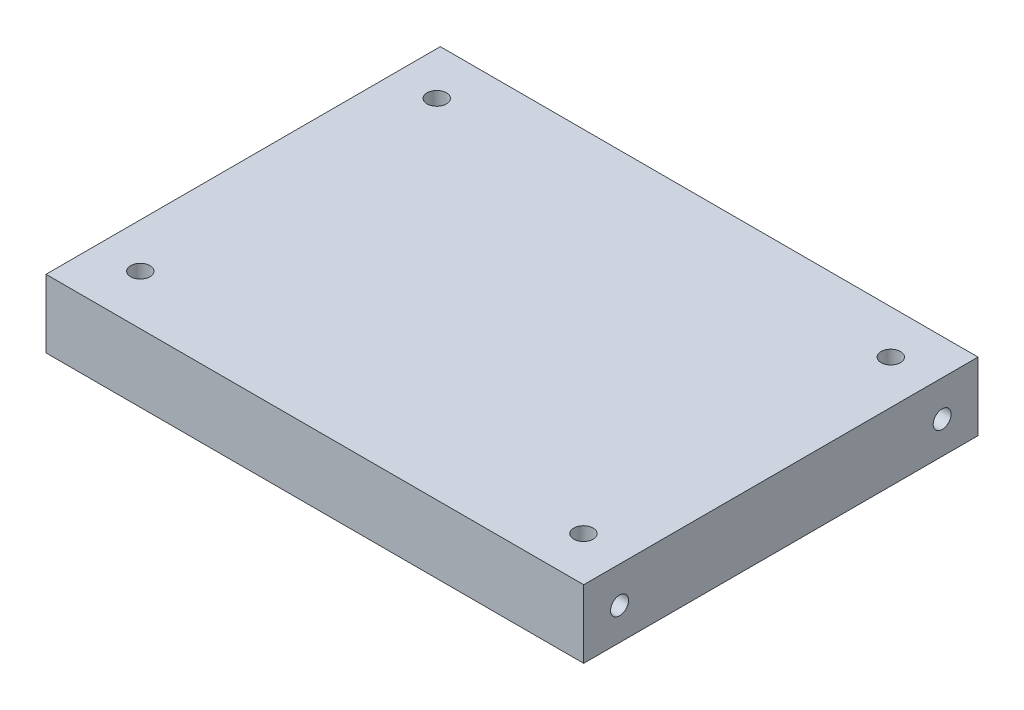
SolidWorks part; units mm, degrees
ref_plane "Front Plane" through (0, 0, 0) normal (0, 0, 1) x (1, 0, 0)
ref_plane "Top Plane" through (0, 0, 0) normal (0, 1, 0) x (1, 0, 0)
ref_plane "Right Plane" through (0, 0, 0) normal (1, 0, 0) x (0, 0, -1)
sketch "Sketch1" plane through (0, 0, 0) normal (0, 1, 0) x (1, 0, 0)
  line L1 (37.5, 27.5) -> (-37.5, 27.5)
  line L2 (37.5, 27.5) -> (37.5, -27.5)
  line L3 (37.5, -27.5) -> (-37.5, -27.5)
  line L4 (-37.5, 27.5) -> (-37.5, -27.5)
  line L5 (0, -27.5) -> (0, 27.5) construction
  line L6 (37.5, 0) -> (-37.5, 0) construction
  point P0 (0, 0)
  dimension "D1" = 55
  dimension "D2" = 75
extrude "Boss-Extrude1" add sketch "Sketch1" along normal blind 9.5
sketch "Sketch2" plane through (0, 9.5, 0) normal (0, 1, 0) x (1, 0, 0)
  line L1 (31.5, 21) -> (-31.5, 21) construction
  line L2 (31.5, 21) -> (31.5, -21) construction
  line L3 (31.5, -21) -> (-31.5, -21) construction
  line L4 (-31.5, 21) -> (-31.5, -21) construction
  line L5 (0, -21) -> (0, 21) construction
  line L6 (31.5, 0) -> (-31.5, 0) construction
  circle A0 centre (-31.5, 21) radius 1.35
  circle A1 centre (31.4206, 21.4157) radius 1.35
  circle A2 centre (31.3065, -21.3464) radius 1.35
  circle A3 centre (-31.2972, -20.5482) radius 1.35
  point P0 (0, 0)
  point P5 (0, 0)
  point P8 (0, 0)
  point P11 (0, 0)
  dimension "D3" = 2.7
  dimension "D1" = 42
  dimension "D2" = 63
extrude "Cut-Extrude1" cut sketch "Sketch2" against normal blind 10
sketch "Sketch3" plane through (-37.5, 0, 0) normal (-1, 0, 0) x (0, 0, 1)
  line L2 (-27.5, 4.5) -> (27.5, 4.5)
  line L3 (-27.5, 4.5) -> (27.5, 4.5) construction
  line L7 (-27.5, 9.5) -> (-27.5, 0) construction
  line L8 (27.5, 9.5) -> (27.5, 0) construction
  point P10 (22.5, 4.5)
  point P11 (-22.5, 4.5)
  dimension "D2" = 5
  dimension "D3" = 5
  dimension "D1" = 4.5
hole_wizard "M3x0.5 Tapped Hole2" positions "Sketch3" profile "Sketch5" tap size "M3x0.5" standard "ANSI Metric"
sketch "Sketch5" plane through (-37.5, 4.5, -22.5) normal (0, 1, 0) x (0, 0, 1)
  line L0 (0, 0) -> (0, 3.7511)
  line L1 (0, 3.7511) -> (1.25, 3)
  line L2 (1.25, 3) -> (1.25, 0)
  line L5 (1.25, 0) -> (0, 0)
  line L10 (0, 3.7511) -> (-1.25, 3) construction
  line L11 (0, -6.35) -> (0, 107.95) construction
  dimension "Tap Drill Dia." = 2.5
  dimension "Tap Drill Depth" = 3
  dimension "Drill Angle" = 118
cosmetic thread "Hole Thread7" parameters "D1"=25, "D2"=3
cosmetic thread "Hole Thread8" parameters "D1"=25, "D2"=3
sketch "Sketch6" plane through (0, 9.5, 0) normal (0, 1, 0) x (1, 0, 0)
  line L0 (0, 27.5) -> (0, -27.5) construction
  line L1 (37.5, 27.5) -> (-37.5, 27.5) construction
  line L2 (-37.5, -27.5) -> (37.5, -27.5) construction
ref_plane "Plane1" through (0, 0, 0) normal (-1, 0, 0) x (0, 0, 1)
mirror "Mirror1" about plane through (0, 0, 0) normal (-1, 0, 0) of "M3x0.5 Tapped Hole2"
cosmetic thread "Hole Thread9" parameters "D1"=25, "D2"=3
cosmetic thread "Hole Thread10" parameters "D1"=25, "D2"=3
